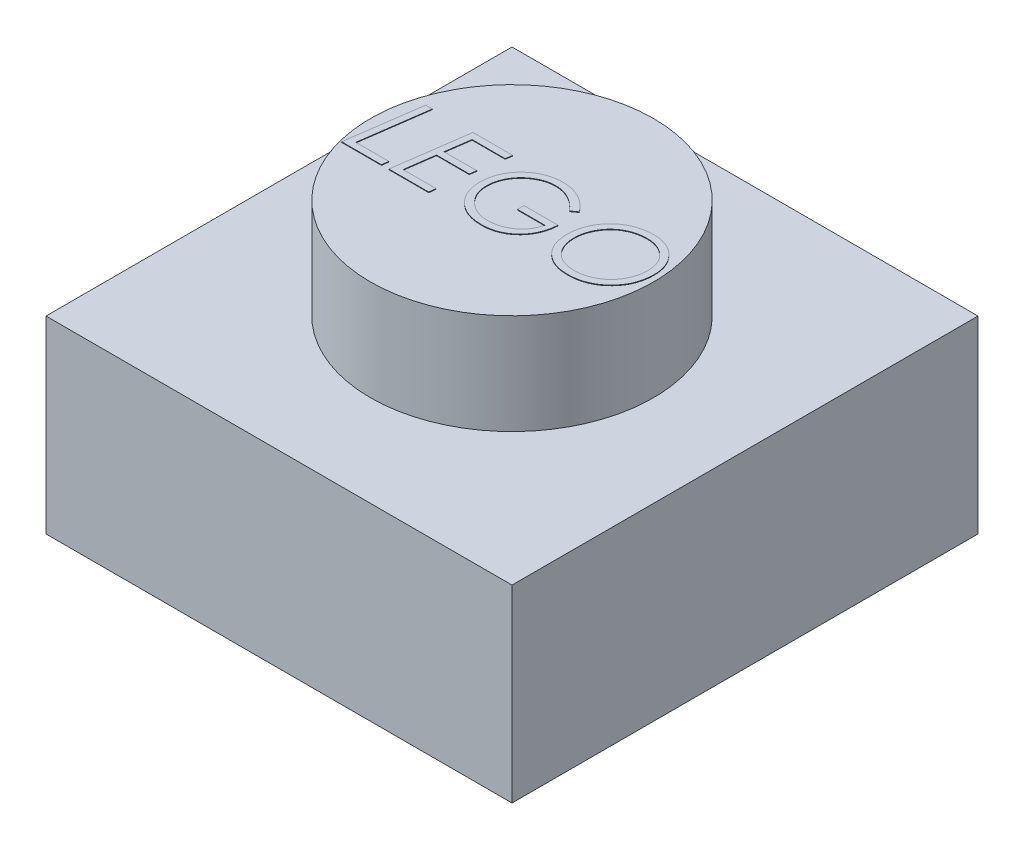
SolidWorks part; units mm, degrees
ref_plane "Front Plane" through (0, 0, 0) normal (0, 0, 1) x (1, 0, 0)
ref_plane "Top Plane" through (0, 0, 0) normal (0, 1, 0) x (1, 0, 0)
ref_plane "Right Plane" through (0, 0, 0) normal (1, 0, 0) x (0, 0, -1)
sketch "Sketch1" plane through (0, 0, 0) normal (0, 1, 0) x (1, 0, 0)
  line L0 (0, 0) -> (7.9, 0)
  line L1 (7.9, 0) -> (7.9, 7.9)
  line L2 (0, 0) -> (0, 7.9)
  line L3 (0, 7.9) -> (7.9, 7.9)
  dimension "D1" = 7.9
  dimension "D2" = 7.9
  dimension "D3" = 7.9
extrude "Boss-Extrude1" add sketch "Sketch1" along normal blind 3.2
sketch "Sketch2" plane through (0, 3.2, 0) normal (0, 1, 0) x (1, 0, 0)
  line L0 (0, 7.9) -> (7.9, 0) construction
  circle A0 centre (3.95, 3.95) radius 2.4
extrude "Boss-Extrude2" add sketch "Sketch2" along normal blind 1.7
sketch "Sketch3" plane through (0, 4.9, 0) normal (0, 1, 0) x (1, 0, 0)
  line L0 (1.625, 3.3549) -> (6.275, 3.3549) construction
  circle A0 centre (3.95, 3.95) radius 2.4 construction
  circle A1 centre (3.95, 3.95) radius 2.4 construction
  text T0 "<i>LEGO</i>" font "Century Gothic" height 1.25
extrude "Boss-Extrude4" add sketch "Sketch3" along normal blind 0.01
sketch "Sketch4" plane through (0, 0, 0) normal (0, -1, 0) x (1, 0, 0)
  line L0 (7.9, -7.9) -> (0, -7.9) construction
  line L1 (7.3, -7.3) -> (0.6204, -7.3)
  line L2 (7.3, -7.3) -> (7.3, -0.6204)
  line L3 (7.3, -0.6204) -> (0.6204, -0.6204)
  line L4 (0.6204, -7.3) -> (0.6204, -0.6204)
  line L5 (7.9, 0) -> (7.9, -7.9) construction
  dimension "D1" = 0.6
  dimension "D2" = 0.6
extrude "Cut-Extrude1" cut sketch "Sketch4" against normal blind 2.01 contours L2 L1 L4 L3
sketch "Sketch5" plane through (0, 3.2, 0) normal (0, 1, 0) x (1, 0, 0)
  line L1 (1.4581, 1.5578) -> (6.3695, 1.5578)
  line L2 (1.4581, 1.5578) -> (1.4581, 6.3652)
  line L3 (1.4581, 6.3652) -> (6.3695, 6.3652)
  line L4 (6.3695, 1.5578) -> (6.3695, 6.3652)
  circle A1 centre (6.3695, 6.3652) radius 1.0161
  circle A2 centre (6.3695, 1.5578) radius 1.0061
  circle A3 centre (1.4581, 1.5578) radius 1.0219
  circle A4 centre (1.4581, 6.3652) radius 1.0411
  circle M5 centre (3.95, 3.95) radius 2.4
extrude "Boss-Extrude5" add sketch "Sketch5" against normal blind 2.01 contours L1 A2 L4 | L2 A3 L1 | L1 A3 L2 | L4 A2 L1 M5 | L4 A1 L3 | L3 A1 L4 | L2 A4 L3 | L3 A4 L2
